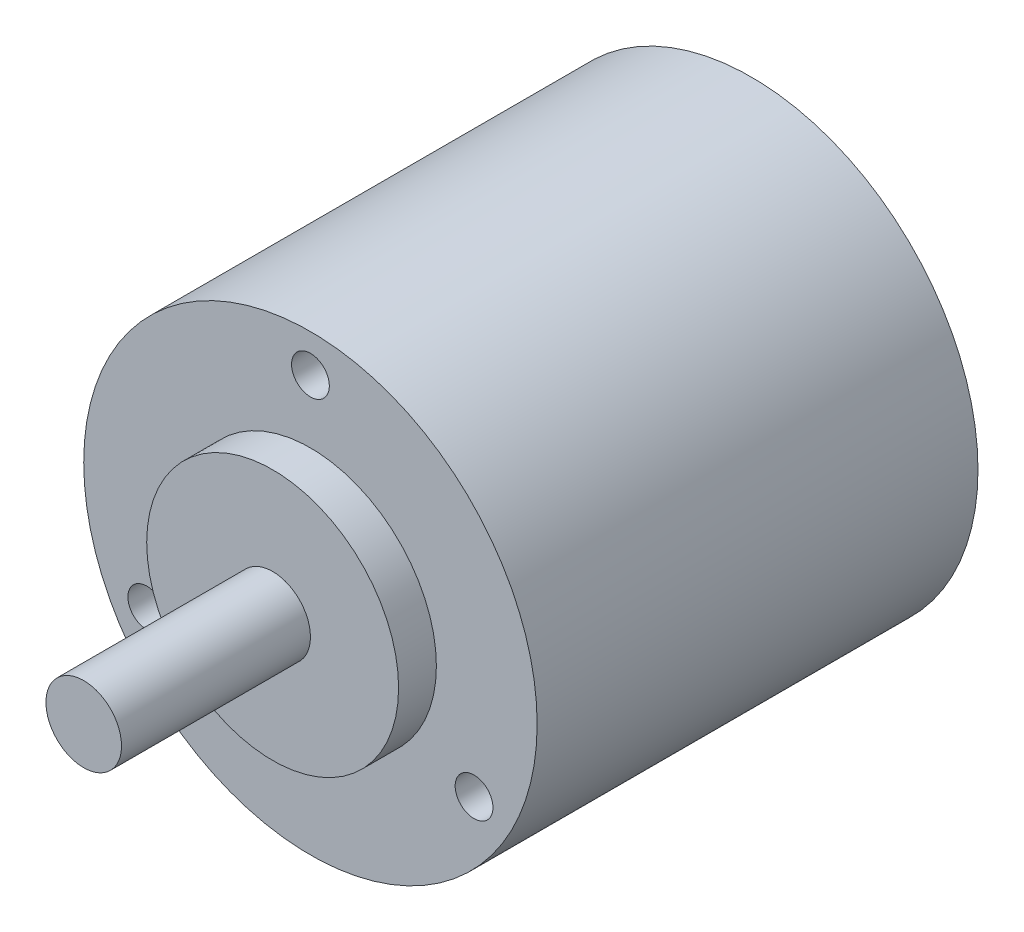
SolidWorks part; units mm, degrees
material "1060 Alloy"
ref_plane "Front Plane" through (0, 0, 0) normal (0, 0, 1) x (1, 0, 0)
ref_plane "Top Plane" through (0, 0, 0) normal (0, 1, 0) x (1, 0, 0)
ref_plane "Right Plane" through (0, 0, 0) normal (1, 0, 0) x (0, 0, -1)
sketch "Sketch1" plane through (0, 0, 0) normal (0, 0, 1) x (1, 0, 0)
  circle A0 centre (0, 0) radius 18
  dimension "D1" = 36
extrude "Boss-Extrude1" add sketch "Sketch1" along normal blind 35
sketch "Sketch2" plane through (0, 0, 35) normal (0, 0, 1) x (1, 0, 0)
  circle A0 centre (0, 0) radius 10
  dimension "D1" = 20
extrude "Boss-Extrude2" add sketch "Sketch2" along normal blind 3
sketch "Sketch3" plane through (0, 0, 38) normal (0, 0, 1) x (1, 0, 0)
  circle A0 centre (0, 0) radius 3
  dimension "D1" = 6
extrude "Boss-Extrude3" add sketch "Sketch3" along normal blind 15
sketch "Sketch4" plane through (0, 0, 35) normal (0, 0, 1) x (1, 0, 0)
  circle A0 centre (0, 15) radius 1.5
  circle A1 centre (0, 0) radius 3 construction
  circle A2 centre (12.9904, -7.5) radius 1.5
  circle A3 centre (-12.9904, -7.5) radius 1.5
  point P11 (0, 0)
  dimension "D1" = 3
  dimension "D2" = 15
  dimension "D3" = 3
extrude "Cut-Extrude1" cut sketch "Sketch4" against normal blind 15
